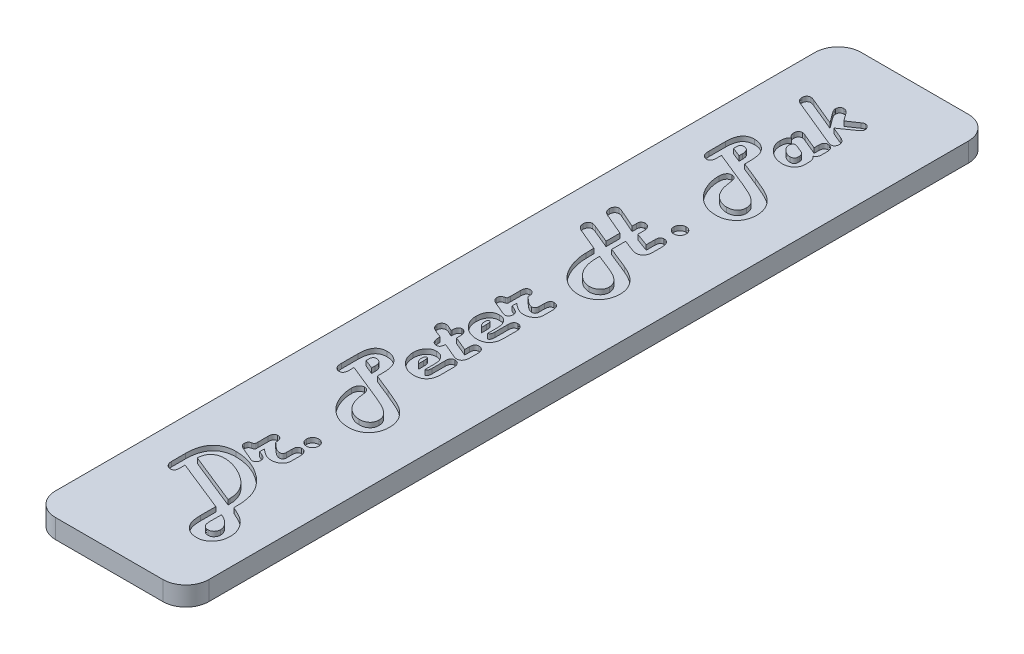
SolidWorks part; units mm, degrees
ref_plane "Front Plane" through (0, 0, 0) normal (0, 0, 1) x (1, 0, 0)
ref_plane "Top Plane" through (0, 0, 0) normal (0, 1, 0) x (1, 0, 0)
ref_plane "Right Plane" through (0, 0, 0) normal (1, 0, 0) x (0, 0, -1)
sketch "Sketch1" plane through (0, 0, 0) normal (0, 0, 1) x (1, 0, 0)
  line L0 (0, 1.5875) -> (0, -1.5875)
  line L1 (-12.7, 0) -> (12.7, 0) construction
  point P6 (0, 0)
  dimension "Width" = 25.4
  dimension "Thk" = 3.175
sketch "Sketch2" plane through (0, 0, 0) normal (1, 0, 0) x (0, 0, -1)
  line L0 (66.675, 0) -> (-66.675, 0)
  point P4 (0, 0)
  dimension "Length" = 133.35
sketch "Sketch3" plane through (0, 0, 0) normal (0, 0, 1) x (1, 0, 0)
  line L1 (12.7, 1.5875) -> (-12.7, 1.5875)
  line L2 (12.7, 1.5875) -> (12.7, -1.5875)
  line L3 (12.7, -1.5875) -> (-12.7, -1.5875)
  line L4 (-12.7, 1.5875) -> (-12.7, -1.5875)
  line L5 (12.7, 1.5875) -> (-12.7, -1.5875) construction
  line L6 (12.7, -1.5875) -> (-12.7, 1.5875) construction
  point P0 (0, 0)
extrude "Boss-Extrude1" add sketch "Sketch3" along normal up to vertex (66.675 mm away) and the other way up to vertex (66.675 mm away) up to point (0, 0, 66.675) other way up to point (0, 0, -66.675)
sketch "Sketch5" plane through (0, 1.5875, 0) normal (0, 1, 0) x (1, 0, 0)
  line L0 (-9.398, 66.929) -> (9.652, 66.929) construction
  line L1 (12.954, 63.627) -> (12.954, -63.373) construction
  line L2 (9.652, -66.675) -> (-9.398, -66.675) construction
  line L3 (-12.7, -63.373) -> (-12.7, 63.627) construction
  line L12 (12.7, -66.675) -> (12.7, 66.675)
  line L13 (12.7, 66.675) -> (-12.7, 66.675)
  line L14 (-12.7, 66.675) -> (-12.7, -66.675)
  line L15 (-12.7, -66.675) -> (12.7, -66.675)
  line L16 (12.7, -62.865) -> (12.7, 62.865)
  line L17 (8.89, 66.675) -> (-8.89, 66.675)
  line L18 (-12.7, 62.865) -> (-12.7, -62.865)
  line L19 (-8.89, -66.675) -> (8.89, -66.675)
  arc A0 (9.652, -66.675) -> (12.954, -63.373) centre (9.652, -63.373) ccw construction
  arc A1 (9.652, -66.675) -> (12.954, -63.373) centre (9.652, -63.373) ccw construction
  arc A2 (-12.7, -63.373) -> (-9.398, -66.675) centre (-9.398, -63.373) ccw construction
  arc A3 (-12.7, -63.373) -> (-9.398, -66.675) centre (-9.398, -63.373) ccw construction
  arc A4 (12.954, 63.627) -> (9.652, 66.929) centre (9.652, 63.627) ccw construction
  arc A5 (12.954, 63.627) -> (9.652, 66.929) centre (9.652, 63.627) ccw construction
  arc A6 (-9.398, 66.929) -> (-12.7, 63.627) centre (-9.398, 63.627) ccw construction
  arc A7 (-9.398, 66.929) -> (-12.7, 63.627) centre (-9.398, 63.627) ccw construction
  arc A8 (12.7, 62.865) -> (8.89, 66.675) centre (8.89, 62.865) ccw
  arc A9 (-8.89, 66.675) -> (-12.7, 62.865) centre (-8.89, 62.865) ccw
  arc A10 (12.7, -62.865) -> (8.89, -66.675) centre (8.89, -62.865) cw
  arc A11 (-8.89, -66.675) -> (-12.7, -62.865) centre (-8.89, -62.865) cw
  dimension "D2" = 3.81
  dimension "D1" = 0
extrude "Cut-Extrude2" cut sketch "Sketch5" against normal through all flip side to cut
sketch "Sketch4" plane through (0, 1.5875, 0) normal (0, 1, 0) x (1, 0, 0)
  line L0 (0, 0) -> (2.54, 0) construction
  line L1 (2.54, -66.675) -> (2.54, 66.675) construction
  line L2 (8.89, 66.675) -> (-8.89, 66.675) construction
  text T0 "Dr. Peter H. Pak" font "Harlow Solid Italic" height 10
  point P8 (2.54, 0)
  dimension "D1" = 2.54
extrude "Cut-Extrude1" cut sketch "Sketch4" against normal blind 0.7937
